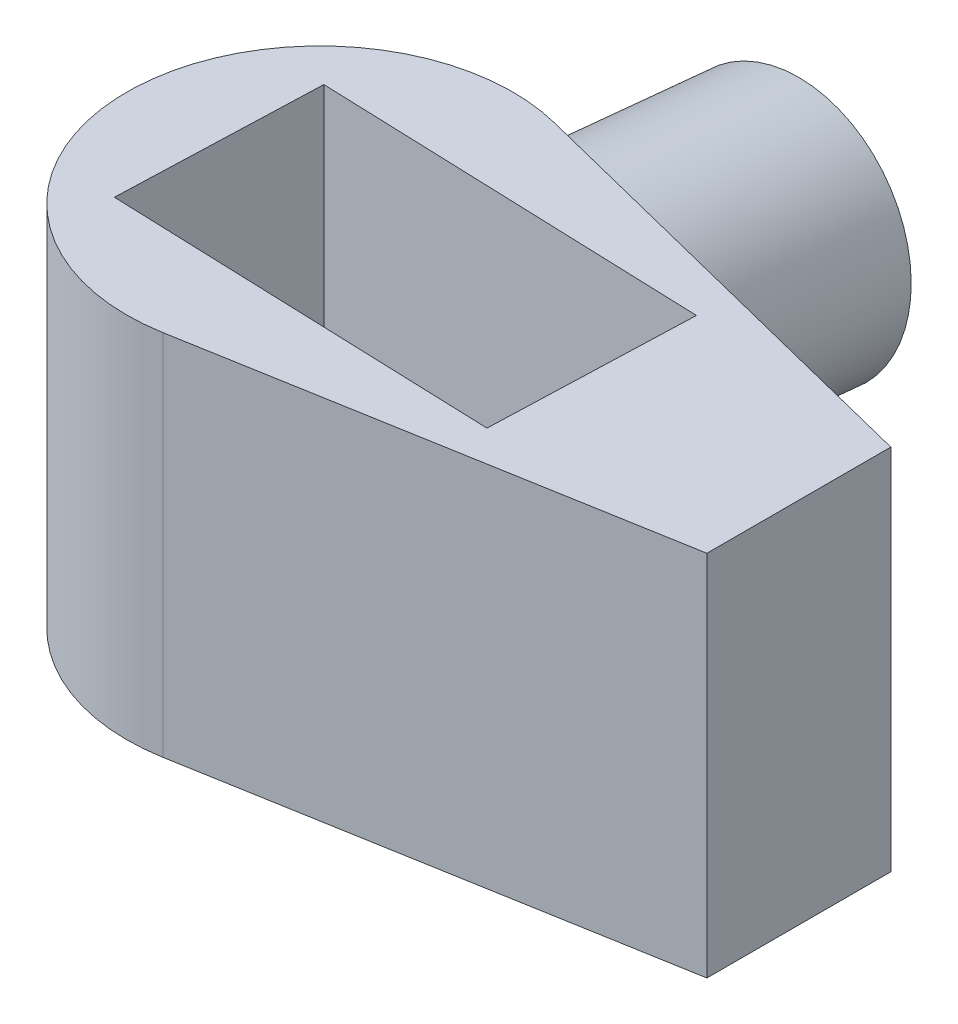
SolidWorks part; units mm, degrees
material "3.0205 (EN-AW 1200)"
ref_plane "Alzado" through (0, 0, 0) normal (0, 0, 1) x (1, 0, 0)
ref_plane "Planta" through (0, 0, 0) normal (0, 1, 0) x (1, 0, 0)
ref_plane "Vista lateral" through (0, 0, 0) normal (1, 0, 0) x (0, 0, -1)
sketch "Croquis1" plane through (0, 0, 0) normal (0, 1, 0) x (1, 0, 0)
  circle A0 centre (0, 0) radius 21
  dimension "D1" = 42
extrude "Saliente-Extruir1" add sketch "Croquis1" along normal blind 40
sketch "Croquis2" plane through (0, 0, 0) normal (0, 1, 0) x (1, 0, 0)
  line L0 (53.9751, 8.111) -> (53.9751, -11.889)
  line L1 (53.9751, -11.889) -> (3.6138, -20.6867)
  line L2 (53.9751, 8.111) -> (5.1095, 20.3689)
  circle A0 centre (0, 0) radius 21 construction
  arc A1 (3.6138, -20.6867) -> (5.1095, 20.3689) centre (0, 0) ccw
  dimension "D1" = 20
extrude "Saliente-Extruir2" add sketch "Croquis2" along normal blind 40
sketch "Croquis3" plane through (5.1095, 0, -20.3689) normal (0.2433, 0, -0.9699) x (-0.9699, 0, -0.2433)
  line L0 (0, 40) -> (0, 0) construction
  circle A0 centre (0, 20) radius 10
  circle A1 centre (0, 20) radius 13.5
  dimension "D1" = 20
  dimension "D2" = 27
extrude "Saliente-Extruir3" add sketch "Croquis3" against normal up to surface (2.5338 mm away)
ref_plane "Plano1" through (5.1, 0, 0) normal (1, 0, 0) x (0, 0, -1)
sketch "Croquis4" plane through (5.1, 0, 0) normal (1, 0, 0) x (0, 0, -1)
  line L0 (20.3689, 6.46) -> (14.1368, 7.0625)
  line L2 (20.3689, 6.5) -> (20.3689, 0) construction
  line L3 (20.3689, 6.46) -> (44.367, 4.14)
  line L4 (44.367, 4.14) -> (44.367, 7.68)
  line L5 (44.367, 7.68) -> (20.3689, 10)
  line L6 (14.1368, 7.0625) -> (14.4759, 10.5697)
  line L7 (20.3689, 20) -> (48.9072, 17.2411) construction
  line L8 (20.3689, 30) -> (20.3689, 10) construction
  line L9 (14.4759, 10.5697) -> (20.3689, 10)
  spline S0 degree 3 poles (20.3689, 10) (20.4494, 10) (20.5223, 10.0164) (20.6529, 10.0823) (20.7108, 10.1324) (20.8588, 10.3301) (20.9241, 10.5239) (20.9801, 10.9044) (20.9917, 11.0472) (21.002, 11.3586) (21.0007, 11.527) (20.981, 12.0693) (20.9464, 12.4815) (20.8509, 13.4014) (20.7912, 13.8986) (20.6973, 14.7014) (20.6653, 14.9786) (20.602, 15.5533) (20.5707, 15.8513) (20.4835, 16.756) (20.4335, 17.3799) (20.3636, 18.6723) (20.344, 19.3468) (20.3447, 20.6893) (20.3643, 21.3468) (20.4171, 22.3143) (20.4385, 22.6336) (20.4878, 23.2659) (20.5154, 23.5761) (20.6029, 24.4783) (20.6679, 25.0473) (20.7624, 25.855) (20.7933, 26.1161) (20.8506, 26.6134) (20.8772, 26.8508) (20.9241, 27.3042) (20.9443, 27.52) (20.9765, 27.9301) (20.9883, 28.1252) (21.0073, 28.6684) (20.9982, 28.9748) (20.9423, 29.3516) (20.9166, 29.4632) (20.8492, 29.6573) (20.8074, 29.7393) (20.6597, 29.9344) (20.5306, 30) (20.3689, 30) knots 0 0 0 0 0.03125 0.03125 0.0625 0.0625 0.125 0.125 0.15625 0.15625 0.1875 0.1875 0.25 0.25 0.3125 0.3125 0.34375 0.34375 0.375 0.375 0.4375 0.4375 0.5 0.5 0.5625 0.5625 0.59375 0.59375 0.625 0.625 0.6875 0.6875 0.71875 0.71875 0.75 0.75 0.78125 0.78125 0.8125 0.8125 0.875 0.875 0.90625 0.90625 0.9375 0.9375 1 1 1 1 construction
  dimension "D2" = 24.11
sketch "Croquis7" plane through (0, 0, 0) normal (0, -1, 0) x (1, 0, 0)
  circle A0 centre (0, 0) radius 6
  circle A1 centre (0, 0) radius 8.2273
  dimension "D1" = 16.4545
  dimension "D2" = 12
extrude "Cortar-Extruir6" cut sketch "Croquis7" against normal blind 6
sketch "Croquis8" plane through (0, 0, 0) normal (0, -1, 0) x (1, 0, 0)
  circle A0 centre (0, 0) radius 6
extrude "Cortar-Extruir7" cut sketch "Croquis8" against normal through all
sketch "Croquis10" plane through (0, 40, 0) normal (0, 1, 0) x (1, 0, 0)
  line L0 (-11.3782, 0.4245) -> (30.6218, -1.0623)
  line L1 (-10.9888, 11.4245) -> (31.0112, 9.9377)
  line L2 (-10.9888, 11.4245) -> (-11.7676, -10.5755)
  line L3 (31.0112, 9.9377) -> (30.2324, -12.0623)
  line L4 (-11.7676, -10.5755) -> (30.2324, -12.0623)
  line L5 (37.4945, -5.951) -> (37.4945, -5.9648)
  line L7 (53.9751, -1.889) -> (-20.9861, 0.7646)
  line L8 (53.9751, -11.889) -> (53.9751, 8.111) construction
  arc A0 (5.1095, 20.3689) -> (3.6138, -20.6867) centre (0, 0) ccw construction
  point P7 (16.4945, -0.5622)
  circle M7 centre (0, 0) radius 6
  dimension "D1" = 11
  dimension "D2" = 42
extrude "Cortar-Extruir8" cut sketch "Croquis10" against normal blind 25 contours L2 L4 L3 L0 M7 | L3 L1 L2 L0 M7
sketch "Croquis12" plane through (0, 15, 0) normal (0, 1, 0) x (1, 0, 0)
  circle A0 centre (0, 0) radius 9.55
  dimension "D1" = 19.1
extrude "Cortar-Extruir9" cut sketch "Croquis12" against normal blind 5.5
revolve "Revolución1" add sketch "Croquis4" angle 360 about L7
